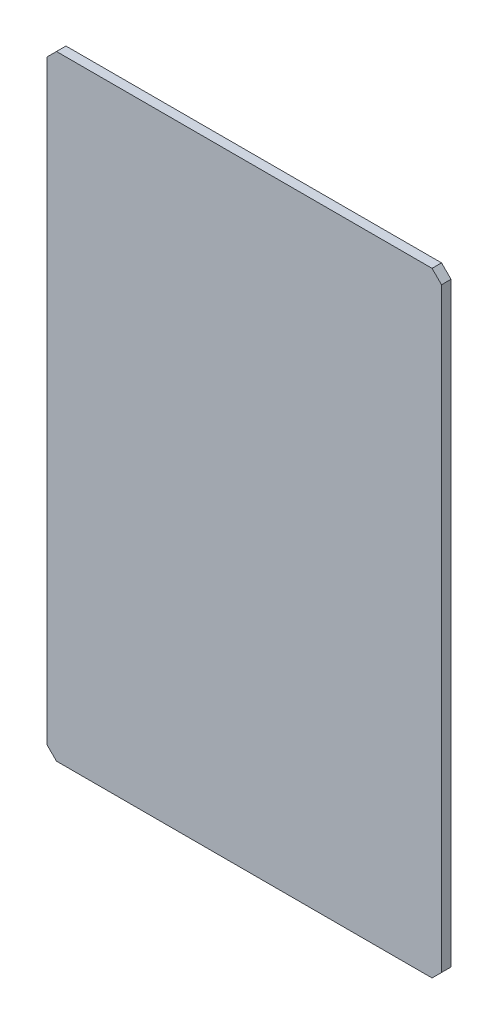
SolidWorks part; units mm, degrees
ref_plane "Front Plane" through (0, 0, 0) normal (0, 0, 1) x (1, 0, 0)
ref_plane "Top Plane" through (0, 0, 0) normal (0, 1, 0) x (1, 0, 0)
ref_plane "Right Plane" through (0, 0, 0) normal (1, 0, 0) x (0, 0, -1)
sketch "Sketch1" plane through (0, 0, 0) normal (0, 0, 1) x (1, 0, 0)
  line L0 (106.5, 5) -> (29.5, 5) construction
  line L1 (-80.5, 25) -> (127.5, 25)
  line L2 (-80.5, 25) -> (-80.5, -299)
  line L3 (-80.5, -299) -> (127.5, -299)
  line L4 (127.5, 25) -> (127.5, -299)
  line L5 (-60.5, -61) -> (-60.5, -277) construction
  line L6 (107.5, -197) -> (107.5, -61) construction
  line L7 (-58.5, -279) -> (16.5, -279) construction
  dimension "D1" = 20
  dimension "D2" = 20
  dimension "D3" = 20
  dimension "D4" = 20
extrude "Boss-Extrude1" add sketch "Sketch1" along normal blind 5
chamfer "Chamfer1" distance 5 angle 45 4 edges at (-80.5, 25, 2.5) (127.5, 25, 2.5) (-80.5, -299, 2.5) (127.5, -299, 2.5)
